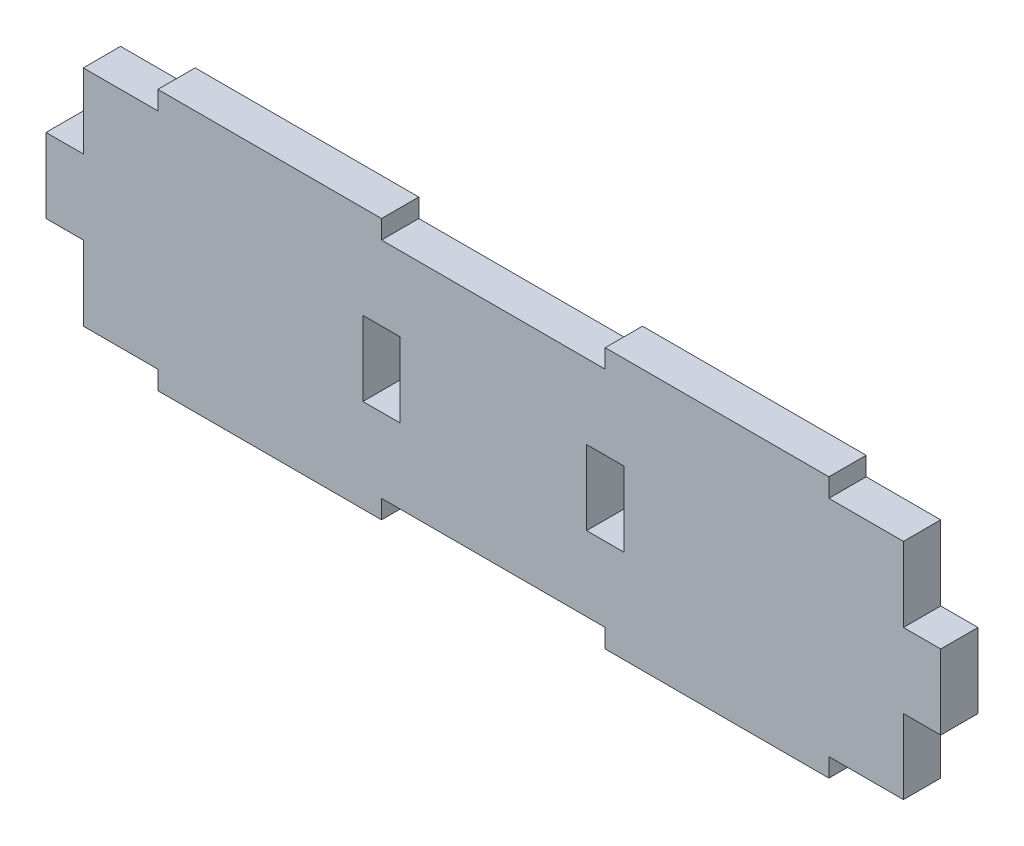
SolidWorks part; units mm, degrees
ref_plane "Front Plane" through (0, 0, 0) normal (0, 0, 1) x (1, 0, 0)
ref_plane "Top Plane" through (0, 0, 0) normal (0, 1, 0) x (1, 0, 0)
ref_plane "Right Plane" through (0, 0, 0) normal (1, 0, 0) x (0, 0, -1)
sketch "Sketch1" plane through (0, 0, 0) normal (0, 0, 1) x (1, 0, 0)
  line L1 (-152.4, -38.1) -> (152.4, -38.1)
  line L2 (-152.4, -38.1) -> (-152.4, 38.1)
  line L3 (-152.4, 38.1) -> (152.4, 38.1)
  line L4 (152.4, -38.1) -> (152.4, 38.1)
  line L5 (-152.4, -38.1) -> (152.4, 38.1) construction
  line L6 (-152.4, 38.1) -> (152.4, -38.1) construction
  point P0 (0, 0)
  dimension "D1" = 304.8
  dimension "D2" = 76.2
extrude "Boss-Extrude1" add sketch "Sketch1" along normal blind 12.7
sketch "Sketch2" plane through (0, 0, 12.7) normal (0, 0, 1) x (1, 0, 0)
  line L0 (-152.4, -38.1) -> (152.4, -38.1) construction
  line L1 (-38.1, -38.1) -> (-114.3, -38.1)
  line L2 (-38.1, -38.1) -> (-38.1, -44.45)
  line L3 (-38.1, -44.45) -> (-114.3, -44.45)
  line L4 (-114.3, -38.1) -> (-114.3, -44.45)
  line L5 (0, -55) -> (0, 55) construction
  line L6 (38.1, -44.45) -> (114.3, -44.45)
  line L7 (114.3, -38.1) -> (114.3, -44.45)
  line L8 (38.1, -38.1) -> (114.3, -38.1)
  line L9 (38.1, -38.1) -> (38.1, -44.45)
  line L10 (55, 0) -> (-55, 0) construction
  line L11 (38.1, 38.1) -> (38.1, 44.45)
  line L12 (38.1, 38.1) -> (114.3, 38.1)
  line L13 (114.3, 38.1) -> (114.3, 44.45)
  line L14 (38.1, 44.45) -> (114.3, 44.45)
  line L15 (-38.1, 44.45) -> (-114.3, 44.45)
  line L16 (-114.3, 38.1) -> (-114.3, 44.45)
  line L17 (-38.1, 38.1) -> (-114.3, 38.1)
  line L18 (-38.1, 38.1) -> (-38.1, 44.45)
  point P12 (-38.1, -41.275)
  dimension "D1" = 76.2
  dimension "D2" = 6.35
  dimension "D3" = 76.2
extrude "Boss-Extrude2" add sketch "Sketch2" against normal blind 12.7
sketch "Sketch3" plane through (0, 0, 12.7) normal (0, 0, 1) x (1, 0, 0)
  line L0 (6.985, 0) -> (-6.985, 0) construction
  line L1 (-152.4, -38.1) -> (-139.7, -38.1)
  line L2 (-152.4, -38.1) -> (-152.4, -12.7)
  line L3 (-152.4, -12.7) -> (-139.7, -12.7)
  line L4 (-139.7, -38.1) -> (-139.7, -12.7)
  line L5 (152.4, -38.1) -> (152.4, 38.1) construction
  line L6 (-152.4, 12.7) -> (-139.7, 12.7)
  line L7 (-139.7, 38.1) -> (-139.7, 12.7)
  line L8 (-152.4, 38.1) -> (-139.7, 38.1)
  line L9 (-152.4, 38.1) -> (-152.4, 12.7)
  line L10 (0, -6.985) -> (0, 6.985) construction
  line L11 (152.4, 38.1) -> (152.4, 12.7)
  line L12 (152.4, 38.1) -> (139.7, 38.1)
  line L13 (139.7, 38.1) -> (139.7, 12.7)
  line L14 (152.4, 12.7) -> (139.7, 12.7)
  line L15 (152.4, -12.7) -> (139.7, -12.7)
  line L16 (139.7, -38.1) -> (139.7, -12.7)
  line L17 (152.4, -38.1) -> (139.7, -38.1)
  line L18 (152.4, -38.1) -> (152.4, -12.7)
  line L19 (31.75, 12.7) -> (44.45, 12.7)
  line L20 (31.75, 12.7) -> (31.75, -12.7)
  line L21 (31.75, -12.7) -> (44.45, -12.7)
  line L22 (44.45, 12.7) -> (44.45, -12.7)
  line L23 (-38.1, -38.1) -> (38.1, -38.1) construction
  line L24 (-31.75, -12.7) -> (-44.45, -12.7)
  line L25 (-44.45, 12.7) -> (-44.45, -12.7)
  line L26 (-31.75, 12.7) -> (-44.45, 12.7)
  line L27 (-31.75, 12.7) -> (-31.75, -12.7)
  line L28 (-38.1, 38.1) -> (38.1, 38.1) construction
  dimension "D1" = 25.4
  dimension "D2" = 12.7
  dimension "D3" = 107.95
  dimension "D4" = 12.7
  dimension "D5" = 25.4
  dimension "D6" = 25.4
extrude "Cut-Extrude1" cut sketch "Sketch3" against normal through all
